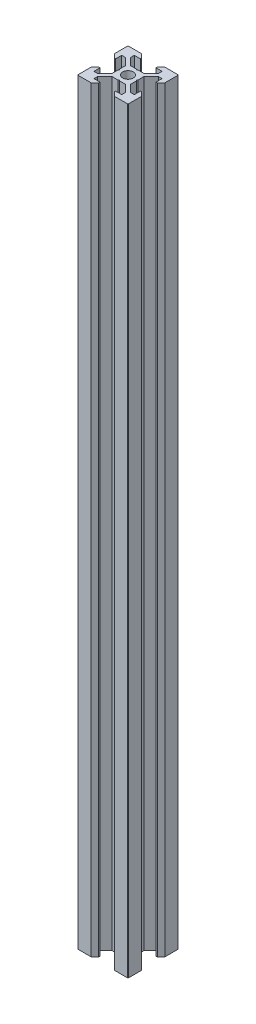
SolidWorks part; units mm, degrees
ref_plane "Plan de face" through (0, 0, 0) normal (0, 0, 1) x (1, 0, 0)
ref_plane "Plan de dessus" through (0, 0, 0) normal (0, 1, 0) x (1, 0, 0)
ref_plane "Plan de droite" through (0, 0, 0) normal (1, 0, 0) x (0, 0, -1)
sketch "Esquisse1" plane through (0, 0, 0) normal (0, 1, 0) x (1, 0, 0)
  line L0 (0, -68.4) -> (0, 76.1968) construction
  line L1 (-68.4, 0) -> (76.1968, 0) construction
  line L2 (0, 0) -> (13.0871, 13.0871) construction
  line L4 (3.7, 2.6393) -> (6.5607, 5.5)
  line L5 (6.5607, 5.5) -> (8, 5.5)
  line L6 (8, 5.5) -> (8, 3.1)
  line L7 (8, 3.1) -> (8.52, 3.1)
  line L8 (8.52, 3.1) -> (10, 4.58)
  line L9 (10, 4.58) -> (10, 9.82)
  line L10 (0.3536, 3.7) -> (0, 3.3464)
  line L60 (3.7, 2.6393) -> (3.7, 0.3536)
  line L61 (3.7, 0.3536) -> (3.3464, 0)
  line L62 (2.6393, 3.7) -> (0.3536, 3.7)
  line L63 (4.58, 10) -> (9.82, 10)
  line L64 (3.1, 8.52) -> (4.58, 10)
  line L65 (3.1, 8) -> (3.1, 8.52)
  line L66 (5.5, 8) -> (3.1, 8)
  line L67 (5.5, 6.5607) -> (5.5, 8)
  line L68 (2.6393, 3.7) -> (5.5, 6.5607)
  line L69 (2.6393, -3.7) -> (5.5, -6.5607)
  line L70 (5.5, -6.5607) -> (5.5, -8)
  line L71 (5.5, -8) -> (3.1, -8)
  line L72 (3.1, -8) -> (3.1, -8.52)
  line L73 (3.1, -8.52) -> (4.58, -10)
  line L74 (4.58, -10) -> (9.82, -10)
  line L75 (3.7, -0.3536) -> (3.3464, 0)
  line L76 (2.6393, -3.7) -> (0.3536, -3.7)
  line L77 (0.3536, -3.7) -> (0, -3.3464)
  line L78 (3.7, -2.6393) -> (3.7, -0.3536)
  line L79 (10, -4.58) -> (10, -9.82)
  line L80 (8.52, -3.1) -> (10, -4.58)
  line L81 (8, -3.1) -> (8.52, -3.1)
  line L82 (8, -5.5) -> (8, -3.1)
  line L83 (6.5607, -5.5) -> (8, -5.5)
  line L84 (3.7, -2.6393) -> (6.5607, -5.5)
  line L85 (-3.7, -2.6393) -> (-6.5607, -5.5)
  line L86 (-6.5607, -5.5) -> (-8, -5.5)
  line L87 (-8, -5.5) -> (-8, -3.1)
  line L88 (-8, -3.1) -> (-8.52, -3.1)
  line L89 (-8.52, -3.1) -> (-10, -4.58)
  line L90 (-10, -4.58) -> (-10, -9.82)
  line L91 (-0.3536, -3.7) -> (0, -3.3464)
  line L92 (-3.7, -2.6393) -> (-3.7, -0.3536)
  line L93 (-3.7, -0.3536) -> (-3.3464, 0)
  line L94 (-2.6393, -3.7) -> (-0.3536, -3.7)
  line L95 (-4.58, -10) -> (-9.82, -10)
  line L96 (-3.1, -8.52) -> (-4.58, -10)
  line L97 (-3.1, -8) -> (-3.1, -8.52)
  line L98 (-5.5, -8) -> (-3.1, -8)
  line L99 (-5.5, -6.5607) -> (-5.5, -8)
  line L100 (-2.6393, -3.7) -> (-5.5, -6.5607)
  line L101 (-2.6393, 3.7) -> (-5.5, 6.5607)
  line L102 (-5.5, 6.5607) -> (-5.5, 8)
  line L103 (-5.5, 8) -> (-3.1, 8)
  line L104 (-3.1, 8) -> (-3.1, 8.52)
  line L105 (-3.1, 8.52) -> (-4.58, 10)
  line L106 (-4.58, 10) -> (-9.82, 10)
  line L107 (-3.7, 0.3536) -> (-3.3464, 0)
  line L108 (-2.6393, 3.7) -> (-0.3536, 3.7)
  line L109 (-0.3536, 3.7) -> (0, 3.3464)
  line L110 (-3.7, 2.6393) -> (-3.7, 0.3536)
  line L111 (-10, 4.58) -> (-10, 9.82)
  line L112 (-8.52, 3.1) -> (-10, 4.58)
  line L113 (-8, 3.1) -> (-8.52, 3.1)
  line L114 (-8, 5.5) -> (-8, 3.1)
  line L115 (-6.5607, 5.5) -> (-8, 5.5)
  line L116 (-3.7, 2.6393) -> (-6.5607, 5.5)
  circle A0 centre (0, 0) radius 2.1
  arc A1 (10, 9.82) -> (9.82, 10) centre (9.82, 9.82) ccw
  arc A2 (9.82, -10) -> (10, -9.82) centre (9.82, -9.82) ccw
  arc A3 (-10, -9.82) -> (-9.82, -10) centre (-9.82, -9.82) ccw
  arc A4 (-9.82, 10) -> (-10, 9.82) centre (-9.82, 9.82) ccw
  point P27 (10, 10)
  point P28 (10, 10)
  point P47 (10, -10)
  point P48 (0, 0)
  point P68 (-10, -10)
  point P69 (0, 0)
  point P74 (0, 0)
  point P92 (-10, 10)
  point P93 (0, 0)
  point P96 (0, 0)
  dimension "D9" = 4.2
  dimension "D11" = 4
  dimension "D10" = 0.18
  dimension "D1" = 45
  dimension "D2" = 4.3
  dimension "D3" = 10
  dimension "D4" = 0.75
  dimension "D5" = 3.1
  dimension "D6" = 5.5
  dimension "D7" = 4.58
  dimension "D8" = 2
  dimension "D12" = 0.5
extrude "Boss.-Extru.1" add sketch "Esquisse1" along normal blind 300
